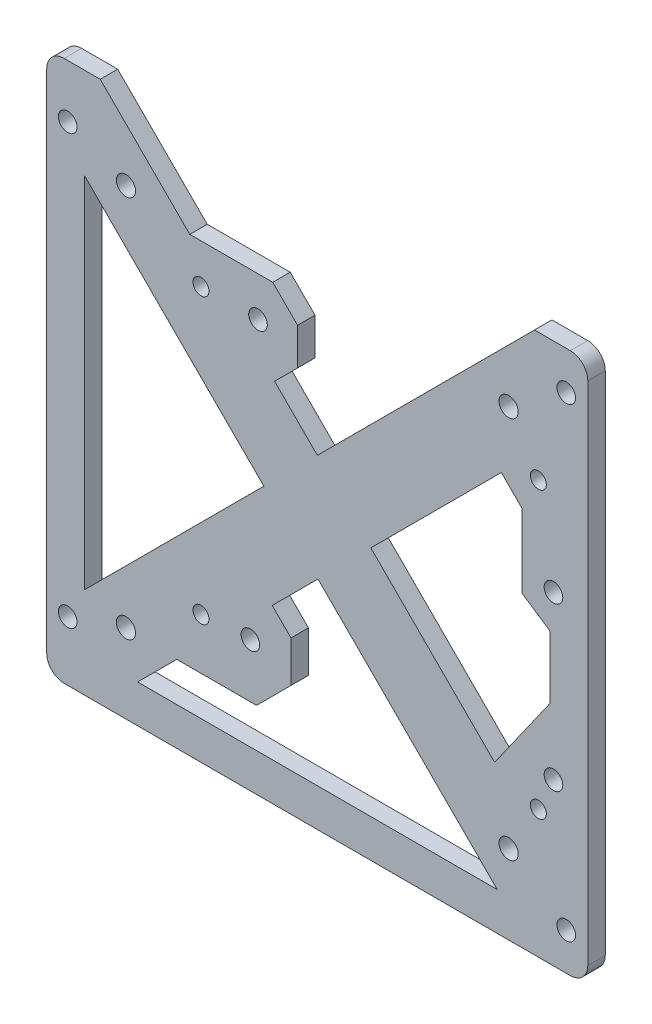
SolidWorks part; units mm, degrees
ref_plane "Front Plane" through (0, 0, 0) normal (0, 0, 1) x (1, 0, 0)
ref_plane "Top Plane" through (0, 0, 0) normal (0, 1, 0) x (1, 0, 0)
ref_plane "Right Plane" through (0, 0, 0) normal (1, 0, 0) x (0, 0, -1)
sketch "Sketch1" plane through (0, 0, 0) normal (0, 0, 1) x (1, 0, 0)
  line L1 (-46.4872, 46.5) -> (46.4872, 46.5)
  line L2 (-46.4872, 46.5) -> (-46.4872, -46.5)
  line L3 (-46.4872, -46.5) -> (46.4872, -46.5)
  line L4 (46.4872, 46.5) -> (46.4872, -46.5)
  line L5 (-46.4872, 46.5) -> (46.4872, -46.5) construction
  line L6 (-46.4872, -46.5) -> (46.4872, 46.5) construction
  point P0 (0, 0)
  dimension "D1" = 93
  dimension "D2" = 92.9743
extrude "Boss-Extrude1" add sketch "Sketch1" along normal blind 3
fillet "Fillet1" radius 3 4 edges at (-46.4872, -46.5, 1.5) (46.4872, -46.5, 1.5) (46.4872, 46.5, 1.5) (-46.4872, 46.5, 1.5)
sketch "Sketch2" plane through (0, 0, 3) normal (0, 0, 1) x (1, 0, 0)
  line L4 (-39.9872, -30.8076) -> (-39.9872, 30.8076)
  line L5 (-39.9872, 30.8076) -> (-9.1796, 0)
  line L6 (-9.1796, 0) -> (-39.9872, -30.8076)
  line L7 (-43.4872, -46.5) -> (43.4872, -46.5) construction
  line L8 (-39.9872, 40) -> (-39.9872, -40)
  line L9 (-39.9872, -40) -> (39.9872, -40)
  line L10 (39.9872, -40) -> (39.9872, 40)
  line L11 (39.9872, 40) -> (-39.9872, 40)
  line L12 (-39.9872, 30.8076) -> (-39.9872, -40)
  line L16 (-30.8716, -39.9778) -> (-24.14, -33.2462)
  line L17 (-24.14, -33.2462) -> (-10.44, -33.2462)
  line L18 (-10.44, -33.2462) -> (-4.5144, -27.3206)
  line L19 (-4.5144, -27.3206) -> (-4.5144, -20.2506)
  line L20 (-4.5144, -20.2506) -> (-7.7401, -17.0249)
  line L21 (-7.7401, -17.0249) -> (0.1229, -9.1619)
  line L22 (0.1229, -9.1619) -> (30.9384, -39.9774)
  line L23 (30.9384, -39.9774) -> (-30.8716, -39.9778)
  line L40 (-37.2952, 46.5) -> (-21.9085, 31.1134)
  line L41 (43.4872, 46.5) -> (-43.4872, 46.5) construction
  line L42 (-21.9085, 31.1134) -> (-7.6485, 31.1134)
  line L43 (-7.6485, 31.1134) -> (-3.3847, 26.8495)
  line L44 (-3.3847, 26.8495) -> (-3.3847, 20.4895)
  line L45 (-3.3847, 20.4895) -> (-7.3316, 16.5425)
  line L46 (-7.3316, 16.5425) -> (0.0179, 9.193)
  line L47 (0.0179, 9.193) -> (37.3248, 46.5)
  line L48 (37.3248, 46.5) -> (-37.2952, 46.5)
  line L51 (9.1993, 0.0116) -> (30.4741, -21.2631)
  line L53 (35.1501, 18.9196) -> (35.1501, 6.2796)
  line L54 (9.1993, 0.0116) -> (31.6288, 22.441)
  line L55 (31.6288, 22.441) -> (35.1501, 18.9196)
  line L56 (35.1501, 6.2796) -> (39.9872, 3.0251)
  line L57 (39.9872, 3.0251) -> (39.9872, -7.7449)
  line L58 (39.9872, -7.7449) -> (30.4741, -21.2631)
  line L59 (46.4872, -43.5) -> (46.4872, 43.5) construction
  point P18 (20.414, 11.2263)
  point P21 (18.6714, 27.8465)
  point P29 (-27.5058, -36.612)
  point P34 (0.0334, -39.9776)
  point P41 (0, 0)
  line M48 (43.4872, 46.5) -> (-43.4872, 46.5)
  dimension "D2" = 15.6924
  dimension "D3" = 61.6152
  dimension "D4" = 43.5685
  dimension "D5" = 43.5685
  dimension "D6" = 74.62
  dimension "D7" = 6.192
  dimension "D8" = 61.81
  dimension "D9" = 9.52
  dimension "D10" = 13.7
  dimension "D11" = 8.38
  dimension "D12" = 7.07
  dimension "D13" = 11.12
  dimension "D14" = 21.76
  dimension "D15" = 12.93
  dimension "D16" = 14.26
  dimension "D17" = 31.72
  dimension "D18" = 18.72
  dimension "D19" = 4.98
  dimension "D20" = 12.64
  dimension "D21" = 5.83
  dimension "D22" = 16.53
  dimension "D23" = 10.77
  dimension "D24" = 30.087
  dimension "D25" = 6.03
  dimension "D26" = 6.36
  dimension "D27" = 10.3938
  dimension "D28" = 52.76
  dimension "D29" = 6.5
  dimension "D1" = 6.5
extrude "Cut-Extrude1" cut sketch "Sketch2" against normal blind 3 contours L46 L47 L40 L42 L43 L44 L45 M48 | L6 L5 L4 | L58 L57 L56 L53 L55 L54 L51 | L23 L22 L21 L20 L19 L18 L17 L16
sketch "Sketch3" plane through (0, 0, 3) normal (0, 0, 1) x (1, 0, 0)
  line L0 (-37.2952, 46.5) -> (-43.4872, 46.5) construction
  line L1 (-46.4872, 43.5) -> (-46.4872, -43.5) construction
  circle A0 centre (-42.8872, 37.38) radius 1.6
  circle A1 centre (-32.8772, 32.89) radius 1.65
  circle A2 centre (-19.9872, 24.3) radius 1.375
  circle A3 centre (-10.1872, 24.3) radius 1.6
  point P0 (-42.8872, 37.38)
  point P1 (-32.8772, 32.89)
  point P2 (-19.9872, 24.3)
  point P3 (-10.1872, 24.3)
  dimension "D1" = 9.12
  dimension "D2" = 3.6
  dimension "D3" = 13.61
  dimension "D4" = 13.61
  dimension "D5" = 22.2
  dimension "D6" = 26.5
  dimension "D7" = 36.3
  dimension "D8" = 22.2
extrude "Cut-Extrude2" cut sketch "Sketch3" against normal blind 3
sketch "Sketch4" plane through (0, 0, 3) normal (0, 0, 1) x (1, 0, 0)
  line L0 (-46.4872, 43.5) -> (-46.4872, -43.5) construction
  line L1 (-43.4872, -46.5) -> (43.4872, -46.5) construction
  line L2 (46.4872, -43.5) -> (46.4872, 43.5) construction
  line L3 (43.4872, 46.5) -> (37.3248, 46.5) construction
  circle A0 centre (42.7772, -40.07) radius 1.6
  circle A1 centre (32.8772, -32.89) radius 1.65
  circle A2 centre (37.9872, -24.5) radius 1.375
  circle A3 centre (40.5872, -18.8) radius 1.6
  circle A4 centre (-42.8872, -36.27) radius 1.6
  circle A5 centre (-32.8772, -32.89) radius 1.65
  circle A6 centre (-19.9872, -24.5) radius 1.375
  circle A7 centre (-11.4872, -24) radius 1.6
  circle A8 centre (42.7772, 39.9) radius 1.6
  circle A9 centre (32.8772, 32.89) radius 1.65
  circle A10 centre (37.9872, 24.5) radius 1.375
  circle A11 centre (40.5872, 9.1) radius 1.6
  point P0 (-42.8872, -36.27)
  point P1 (-32.8772, -32.89)
  point P2 (-19.9872, -24.5)
  point P3 (-11.4872, -24)
  point P8 (42.7772, -40.07)
  point P9 (32.8772, -32.89)
  point P10 (37.9872, -24.5)
  point P11 (40.5872, -18.8)
  point P30 (42.7772, 39.9)
  point P31 (32.8772, 32.89)
  point P32 (37.9872, 24.5)
  point P33 (40.5872, 9.1)
  point P34 (42.7772, 39.9)
  dimension "D17" = 6.6
  dimension "D1" = 3.6
  dimension "D2" = 13.61
  dimension "D3" = 26.5
  dimension "D4" = 35
  dimension "D5" = 10.23
  dimension "D6" = 13.61
  dimension "D7" = 22
  dimension "D8" = 22.5
  dimension "D9" = 5.9
  dimension "D10" = 27.7
  dimension "D11" = 8.5
  dimension "D12" = 22
  dimension "D13" = 13.61
  dimension "D14" = 13.61
  dimension "D15" = 3.71
  dimension "D16" = 6.43
  dimension "D18" = 3.71
  dimension "D19" = 13.61
  dimension "D20" = 13.61
  dimension "D21" = 8.5
  dimension "D22" = 22
  dimension "D23" = 5.9
  dimension "D24" = 37.4
extrude "Cut-Extrude3" cut sketch "Sketch4" against normal blind 3
